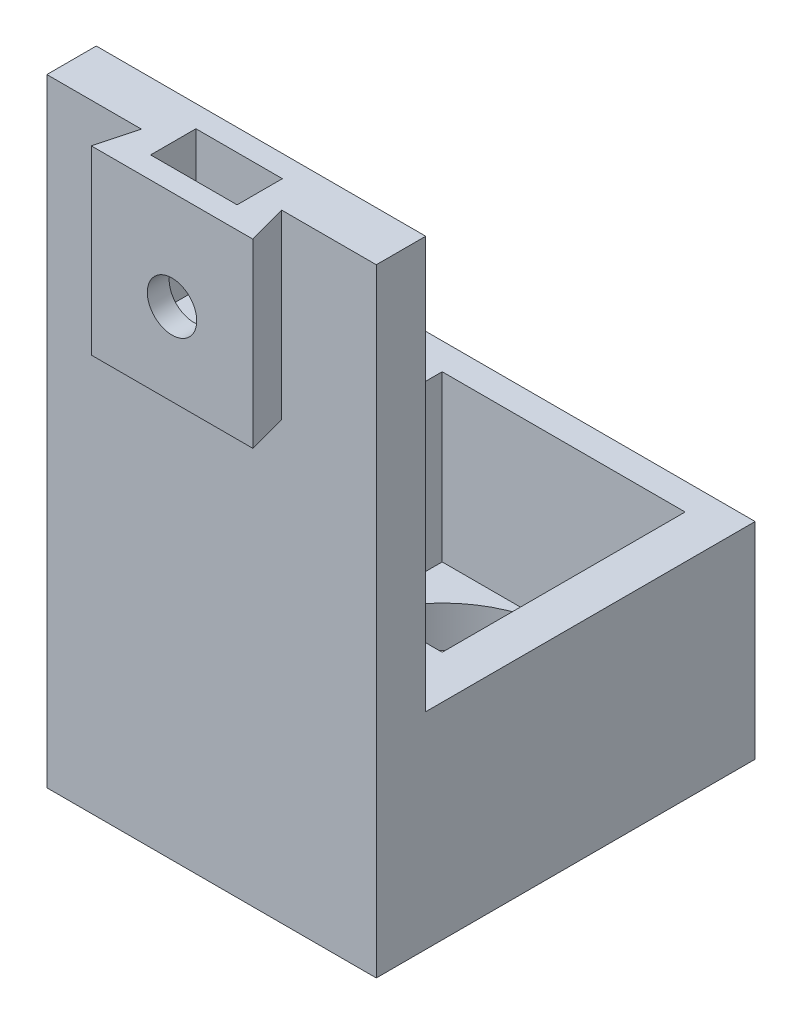
SolidWorks part; units mm, degrees
ref_plane "Ebene vorne" through (0, 0, 0) normal (0, 0, 1) x (1, 0, 0)
ref_plane "Ebene oben" through (0, 0, 0) normal (0, 1, 0) x (1, 0, 0)
ref_plane "Ebene rechts" through (0, 0, 0) normal (1, 0, 0) x (0, 0, -1)
sketch "Skizze1" plane through (0, 0, 0) normal (0, 0, 1) x (1, 0, 0)
  line L0 (0, 112.5849) -> (0, -19.9328) construction
  line L5 (-20, 0) -> (20, 0)
  line L6 (20, 0) -> (20, 75)
  line L7 (20, 75) -> (-20, 75)
  line L8 (-20, 0) -> (-20, 75)
  point P9 (0, 75)
  point P10 (0, 0)
  dimension "D1" = 20
  dimension "D2" = 75
extrude "Aufsatz-Linear austragen1" add sketch "Skizze1" along normal blind 6
sketch "Skizze2" plane through (0, 75, 0) normal (0, 1, 0) x (1, 0, 0)
  line L0 (0, 11.7327) -> (0, -15.213) construction
  line L1 (8.5138, -6) -> (-8.5138, -6)
  line L2 (20, -6) -> (-20, -6) construction
  line L3 (-8.5138, -6) -> (-9.8, -10.8)
  line L4 (-9.8, -10.8) -> (9.8, -10.8)
  line L5 (8.5138, -6) -> (9.8, -10.8)
  point P15 (0, -6)
  point P16 (0, -10.8)
  dimension "D1" = 75
  dimension "D2" = 4.8
  dimension "D3" = 9.8
extrude "Aufsatz-Linear austragen2" add sketch "Skizze2" against normal blind 22
sketch "Skizze3" plane through (0, 75, 0) normal (0, 1, 0) x (1, 0, 0)
  line L0 (0, 8.2528) -> (0, -23.8351) construction
  line L1 (-5.25, -2.65) -> (5.25, -2.65)
  line L2 (-5.25, -2.65) -> (-5.25, -8.15)
  line L3 (-5.25, -8.15) -> (5.25, -8.15)
  line L4 (5.25, -2.65) -> (5.25, -8.15)
  line L5 (-44.3905, -5.4) -> (48.6545, -5.4) construction
  line L6 (-9.8, -10.8) -> (9.8, -10.8) construction
  line L7 (20, 0) -> (-20, 0) construction
  dimension "D1" = 10.5
  dimension "D2" = 5.5
extrude "Schnitt-Linear austragen1" cut sketch "Skizze3" against normal blind 17
sketch "Skizze4" plane through (0, 0, 10.8) normal (0, 0, 1) x (1, 0, 0)
  line L0 (20, 75) -> (-20, 75) construction
  circle A0 centre (0, 63) radius 3
  dimension "D1" = 6
  dimension "D2" = 12
extrude "Schnitt-Linear austragen2" cut sketch "Skizze4" against normal through all
sketch "Skizze5" plane through (0, 0, 0) normal (0, 0, -1) x (-1, 0, 0)
  line L0 (20, 75) -> (20, 0) construction
  line L1 (-20, 0) -> (20, 0)
  line L2 (-20, 0) -> (-20, 25)
  line L3 (-20, 25) -> (20, 25)
  line L4 (20, 0) -> (20, 25)
  dimension "D1" = 25
extrude "Aufsatz-Linear austragen3" add sketch "Skizze5" along normal blind 40
sketch "Skizze6" plane through (0, 25, 0) normal (0, 1, 0) x (1, 0, 0)
  line L0 (0, 52.3978) -> (0, -29.7152) construction
  line L1 (-14.75, 7.25) -> (14.75, 7.25)
  line L2 (-14.75, 7.25) -> (-14.75, 36.75)
  line L3 (-14.75, 36.75) -> (14.75, 36.75)
  line L4 (14.75, 7.25) -> (14.75, 36.75)
  line L5 (-41.8598, 22) -> (38.1111, 22) construction
  line L6 (-20, 40) -> (20, 40) construction
  dimension "D1" = 18
  dimension "D2" = 29.5
  dimension "D3" = 29.5
extrude "Schnitt-Linear austragen3" cut sketch "Skizze6" against normal blind 20
sketch "Skizze7" plane through (0, 5, 0) normal (0, 1, 0) x (1, 0, 0)
  line L0 (14.75, 36.75) -> (-14.75, 36.75) construction
  line L1 (-14.75, 36.75) -> (-14.75, 7.25) construction
  circle A0 centre (0, 22) radius 14.75
  dimension "D1" = 29.5
extrude "Schnitt-Linear austragen4" cut sketch "Skizze7" against normal through all
